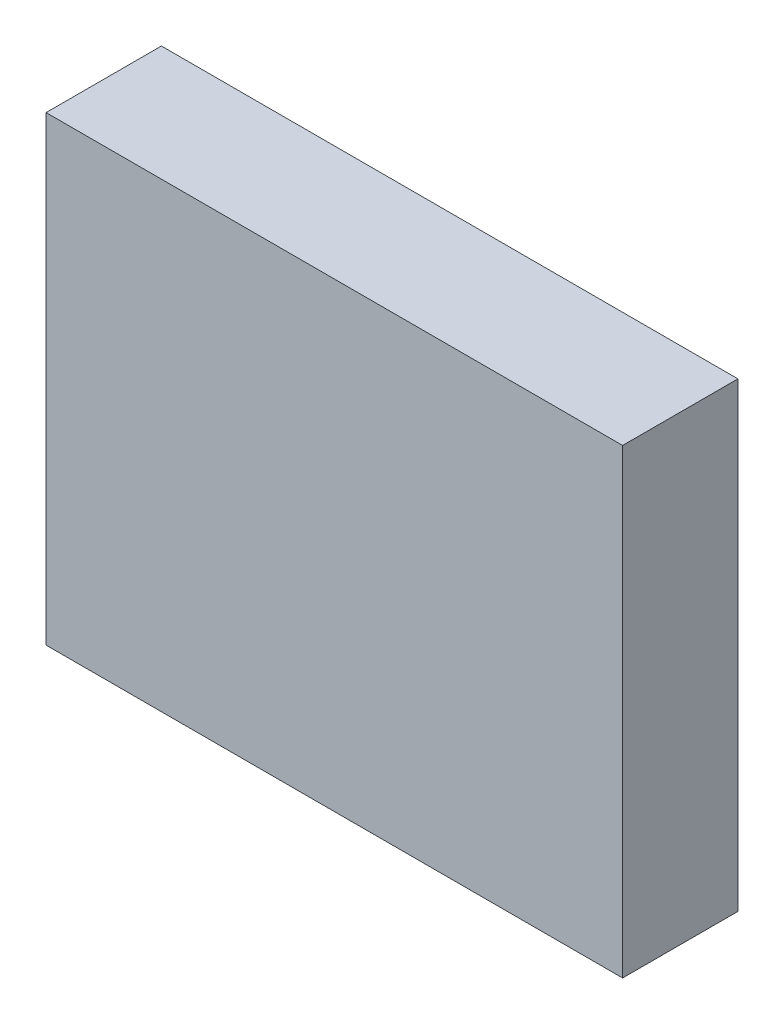
SolidWorks part; units mm, degrees
ref_plane "前视基准面" through (0, 0, 0) normal (0, 0, 1) x (1, 0, 0)
ref_plane "上视基准面" through (0, 0, 0) normal (0, 1, 0) x (1, 0, 0)
ref_plane "右视基准面" through (0, 0, 0) normal (1, 0, 0) x (0, 0, -1)
sketch "草图1" plane through (0, 0, 0) normal (0, 0, 1) x (1, 0, 0)
  line L1 (-12.5, 10) -> (12.5, 10)
  line L2 (-12.5, 10) -> (-12.5, -10)
  line L3 (-12.5, -10) -> (12.5, -10)
  line L4 (12.5, 10) -> (12.5, -10)
  line L5 (-12.5, 10) -> (12.5, -10) construction
  line L6 (-12.5, -10) -> (12.5, 10) construction
  point P0 (0, 0)
  dimension "D1" = 25
  dimension "D2" = 20
extrude "凸台-拉伸1" add sketch "草图1" along normal blind 5
